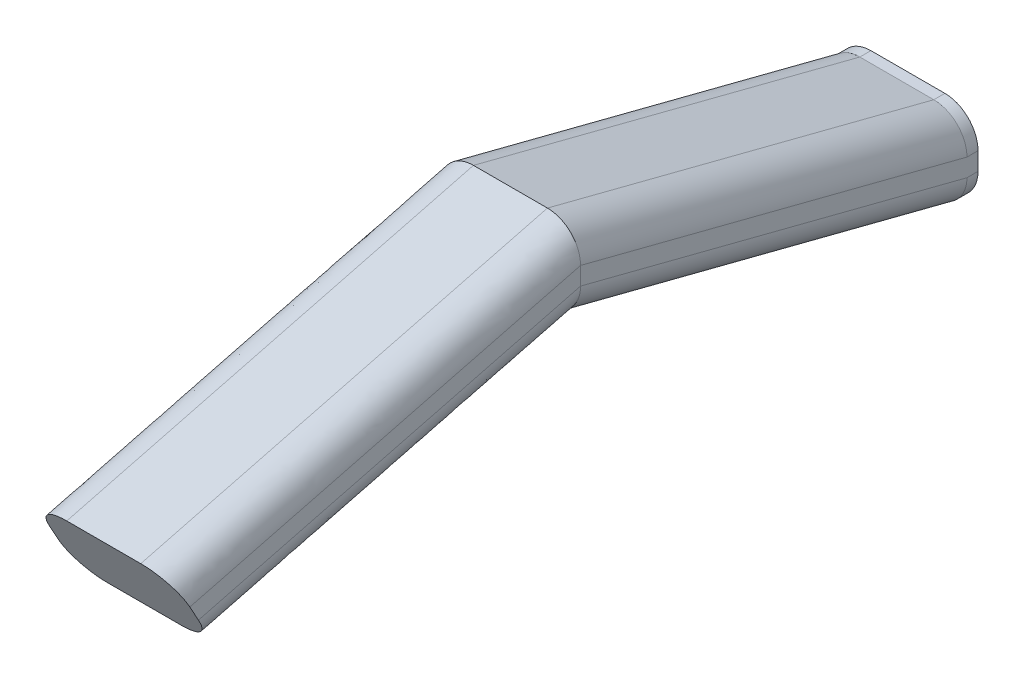
SolidWorks part; units mm, degrees
ref_plane "Alzado" through (0, 0, 0) normal (0, 0, 1) x (1, 0, 0)
ref_plane "Planta" through (0, 0, 0) normal (0, 1, 0) x (1, 0, 0)
ref_plane "Vista lateral" through (0, 0, 0) normal (1, 0, 0) x (0, 0, -1)
sketch "Croquis1" plane through (0, 0, 0) normal (0, 0, 1) x (1, 0, 0)
  line L1 (-33.5, -38.1) -> (33.5, -38.1)
  line L2 (-63.5, -8.1) -> (-63.5, 8.1)
  line L3 (-33.5, 38.1) -> (33.5, 38.1)
  line L4 (63.5, -8.1) -> (63.5, 8.1)
  line L5 (-63.5, -38.1) -> (63.5, 38.1) construction
  line L6 (-63.5, 38.1) -> (63.5, -38.1) construction
  arc A0 (-33.5, -38.1) -> (-63.5, -8.1) centre (-33.5, -8.1) cw
  arc A1 (33.5, -38.1) -> (63.5, -8.1) centre (33.5, -8.1) ccw
  arc A2 (33.5, 38.1) -> (63.5, 8.1) centre (33.5, 8.1) cw
  arc A3 (-63.5, 8.1) -> (-33.5, 38.1) centre (-33.5, 8.1) cw
  point P0 (0, 0)
  dimension "D1" = 127
  dimension "D3" = 30
  dimension "D2" = 76.2
extrude "Saliente-Extruir1" add sketch "Croquis1" along normal blind 10
sketch3d "Croquis3D2"
  line L0 (0, 38.1, 10) -> (0, -38.1, 10) construction
  line L1 (33.5, 38.1, 10) -> (-33.5, 38.1, 10) construction
  line L2 (-33.5, -38.1, 10) -> (33.5, -38.1, 10) construction
  line L3 (0, 0, 10) -> (0, 0, 360) construction
  line L4 (0, 0, 360) -> (0, 90, 360) construction
  line L5 (0, 90, 360) -> (0, 0, 10)
  line L6 (0, 0, 360) -> (0, 0, 710) construction
  line L7 (0, 90, 360) -> (0, 0, 710)
  dimension "D1" = 90
  dimension "D2" = 350
  dimension "D3" = 350
sketch "Croquis3" plane through (0, 0, 10) normal (0, 0, 1) x (1, 0, 0)
  line L1 (33.5, -38.1) -> (-33.5, -38.1)
  line L2 (63.5, -8.1) -> (63.5, 8.1)
  line L3 (33.5, 38.1) -> (-33.5, 38.1)
  line L4 (-63.5, -8.1) -> (-63.5, 8.1)
  line L5 (63.5, -38.1) -> (-63.5, 38.1) construction
  line L6 (63.5, 38.1) -> (-63.5, -38.1) construction
  arc A0 (-33.5, -38.1) -> (-63.5, -8.1) centre (-33.5, -8.1) cw
  arc A1 (33.5, -38.1) -> (63.5, -8.1) centre (33.5, -8.1) ccw
  arc A2 (63.5, 8.1) -> (33.5, 38.1) centre (33.5, 8.1) ccw
  arc A3 (-33.5, 38.1) -> (-63.5, 8.1) centre (-33.5, 8.1) ccw
  point P0 (0, 0)
  dimension "D2" = 30
  dimension "D1" = 127
sweep "Barrer1" add profiles "Croquis3" path "Croquis3D2"
